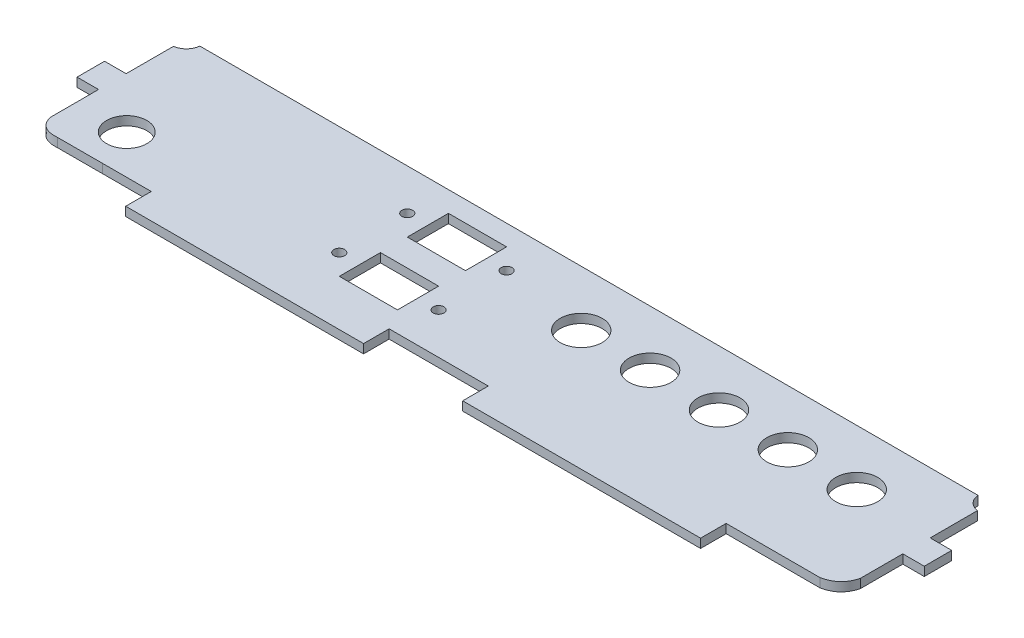
SolidWorks part; units mm, degrees
ref_plane "Front Plane" through (0, 0, 0) normal (0, 0, 1) x (1, 0, 0)
ref_plane "Top Plane" through (0, 0, 0) normal (0, 1, 0) x (1, 0, 0)
ref_plane "Right Plane" through (0, 0, 0) normal (1, 0, 0) x (0, 0, -1)
sketch "Sketch2" plane through (0, -13.2785, 0) normal (0, 1, 0) x (1, 0, 0)
  line L0 (-103.3818, 12.2614) -> (-102.1895, 12.2614) construction
  line L1 (-103.3844, 15.727) -> (-103.3793, 8.7959) construction
  line L2 (-33.2889, 12.2828) -> (-34.6519, 12.2828) construction
  line L3 (-33.2915, 15.7744) -> (-33.2863, 8.7912) construction
  line L4 (-34.6519, 12.2828) -> (-34.6519, 8.7913)
  line L5 (-103.3793, 8.7959) -> (-33.2863, 8.7912) construction
  line L6 (-34.6519, 8.7913) -> (-102.1895, 8.7958)
  line L7 (-116.0844, 15.783) -> (-116.0844, 16.0521) construction
  line L9 (-128.7844, 15.783) -> (-103.3844, 15.783) construction
  line L10 (-116.0844, 16.0521) -> (-102.1895, 16.0521)
  line L11 (-102.1895, 16.0521) -> (-102.1895, 12.2614)
  line L12 (-102.1895, 12.2614) -> (-102.1895, 8.7958)
  line L13 (93.8498, 21.5902) -> (93.5958, 21.5902) construction
  line L14 (-34.6519, 12.2828) -> (-34.6519, 16.0521)
  line L15 (-128.7844, 15.783) -> (-128.7844, 16.037)
  line L17 (93.5958, 21.5902) -> (93.5958, 33.6447)
  line L18 (67.0981, 58.9572) -> (67.0981, 58.7032) construction
  line L28 (90.1543, 58.9557) -> (-131.3147, 58.9704) construction
  line L30 (67.0981, 58.7032) -> (-108.2542, 58.7032)
  line L31 (67.0981, 58.7032) -> (89.8898, 58.7032)
  line L33 (-108.2542, 58.7032) -> (-131.0459, 58.7032)
  line L35 (-20.5781, 8.7904) -> (-20.5781, 74.1189) construction
  line L36 (-7.8698, 8.7896) -> (-33.2863, 8.7912) construction
  line L39 (99.6888, 41.4461) -> (93.5672, 41.4461)
  line L40 (99.6893, 33.6447) -> (99.6888, 41.4461)
  line L41 (96.7684, 33.6447) -> (99.6893, 33.6447)
  line L42 (96.7684, 33.6447) -> (93.5958, 33.6447)
  line L44 (74.9283, 16.0521) -> (87.6283, 16.0521)
  line L45 (74.9283, 16.0521) -> (61.0334, 16.0521)
  line L46 (61.0334, 16.0521) -> (61.0334, 12.2614)
  line L47 (61.0334, 12.2614) -> (61.0334, 8.7958)
  line L48 (-6.5042, 8.7913) -> (61.0334, 8.7958)
  line L49 (-6.5042, 12.2828) -> (-6.5042, 16.0521)
  line L50 (-6.5042, 12.2828) -> (-6.5042, 8.7913)
  line L52 (-34.6519, 16.0521) -> (-6.5042, 16.0521)
  line L53 (-128.7844, 16.037) -> (-116.0844, 16.0521)
  line L54 (93.852, 55.149) -> (93.852, 54.895) construction
  line L55 (93.8512, 42.7342) -> (93.852, 55.149) construction
  line L56 (93.852, 54.895) -> (93.5672, 54.895) construction
  line L57 (93.5672, 54.895) -> (93.5672, 41.4461)
  line L58 (91.7303, 17.7562) -> (91.555, 17.94) construction
  line L59 (-134.7233, 54.895) -> (-134.7233, 41.4461)
  line L60 (-140.8449, 41.4461) -> (-134.7233, 41.4461)
  line L61 (-140.8454, 33.6447) -> (-140.8449, 41.4461)
  line L62 (-137.9245, 33.6447) -> (-140.8454, 33.6447)
  line L63 (-137.9245, 33.6447) -> (-134.7519, 33.6447)
  line L64 (-133.7195, 17.34) -> (-133.5371, 17.5168) construction
  line L65 (-135.0043, 20.0095) -> (-134.7503, 20.0095) construction
  line L66 (-134.7503, 20.0095) -> (-134.7519, 33.6447)
  arc A2 (89.8898, 58.7032) -> (93.5672, 54.895) centre (94.0894, 59.0788) ccw
  arc A4 (-131.0459, 58.7032) -> (-134.7233, 54.895) centre (-135.2455, 59.0788) cw
  parabola Q0 (93.41, 55.3299) -> (93.9736, 52.613) focus (90.4097, 55.3992) apex (92.2035, 57.193) construction
  parabola Q2 (87.6236, 15.783) -> (93.8498, 21.5902) focus (89.4284, 20.1682) apex (91.7303, 17.7562) construction
  parabola Q3 (-128.7844, 15.783) -> (-135.0043, 20.0095) focus (-132.2057, 18.8084) apex (-133.7195, 17.34) construction
  spline S0 degree 2 poles (-134.7503, 20.0095) (-133.7714, 15.691) (-128.7844, 16.037) knots 0 0 0 1 1 1
  spline S1 degree 2 poles (87.6283, 16.0521) (92.3764, 16.9445) (93.5958, 21.5902) knots 0 0 0 1 1 1
  point P33 (-20.5781, 58.7032)
  dimension "D1" = 0.254
  dimension "D2" = 0.2848
extrude "Boss-Extrude1" add sketch "Sketch2" along normal blind 2.54
sketch "Sketch3" plane through (0, -10.7385, 0) normal (0, 1, 0) x (1, 0, 0)
  line L0 (-20.5781, 16.0521) -> (-20.5781, 58.7032) construction
  line L1 (-34.6519, 16.0521) -> (-6.5042, 16.0521) construction
  line L2 (-131.0459, 58.7032) -> (89.8898, 58.7032) construction
  line L3 (-1.0201, 42.9211) -> (6.5999, 42.9211) construction
  line L4 (6.5999, 42.9211) -> (12.5689, 42.9211) construction
  line L5 (-20.5781, 42.9211) -> (-12.9581, 42.9211) construction
  line L6 (-12.9581, 42.9211) -> (-6.9891, 42.9211) construction
  line L7 (18.5379, 42.9211) -> (26.1579, 42.9211) construction
  line L8 (26.1579, 42.9211) -> (32.1269, 42.9211) construction
  line L9 (38.0959, 42.9211) -> (45.7159, 42.9211) construction
  line L10 (45.7159, 42.9211) -> (51.6849, 42.9211) construction
  line L11 (57.6539, 42.9211) -> (65.2739, 42.9211) construction
  line L12 (65.2739, 42.9211) -> (71.2429, 42.9211) construction
  line L13 (71.2429, 36.9521) -> (71.2429, 16.0521) construction
  line L14 (61.0334, 16.0521) -> (87.6283, 16.0521) construction
  line L15 (71.2429, 16.0521) -> (-20.5781, 16.0521) construction
  line L16 (51.6849, 36.9521) -> (51.6849, 16.0521) construction
  line L17 (32.1269, 36.9521) -> (32.1269, 16.0521) construction
  line L18 (12.5689, 36.9521) -> (12.5689, 16.0521) construction
  line L19 (-6.9891, 36.9521) -> (-6.9891, 16.0521) construction
  circle A0 centre (-6.9891, 42.9211) radius 5.969
  circle A1 centre (12.5689, 42.9211) radius 5.969
  circle A2 centre (32.1269, 42.9211) radius 5.969
  circle A3 centre (51.6849, 42.9211) radius 5.969
  circle A4 centre (71.2429, 42.9211) radius 5.969
  dimension "D1" = 11.938
  dimension "D2" = 11.938
  dimension "D3" = 11.938
  dimension "D4" = 11.938
  dimension "D5" = 11.938
  dimension "D6" = 20.9
extrude "Cut-Extrude1" cut sketch "Sketch3" against normal blind 2.54
sketch "Sketch4" plane through (0, -10.7385, 0) normal (0, 1, 0) x (1, 0, 0)
  line L0 (-20.5781, 16.0521) -> (-20.5781, 58.7032) construction
  line L1 (-34.6519, 16.0521) -> (-6.5042, 16.0521) construction
  line L2 (-131.0459, 58.7032) -> (89.8898, 58.7032) construction
  line L3 (-20.5781, 37.3776) -> (-121.2998, 37.3776) construction
  line L4 (-46.3761, 37.3776) -> (-46.3761, 41.1876) construction
  line L5 (-46.3761, 37.3776) -> (-46.3761, 33.5676) construction
  line L6 (-46.3761, 41.1876) -> (-46.3761, 52.8716) construction
  line L7 (-46.3761, 47.0296) -> (-33.8031, 47.0296) construction
  line L8 (-46.3761, 47.0296) -> (-58.9491, 47.0296) construction
  line L9 (-33.8031, 47.0296) -> (-30.7551, 47.0296) construction
  line L10 (-58.9491, 47.0296) -> (-61.9971, 47.0296) construction
  line L11 (-54.6311, 41.1876) -> (-38.1211, 41.1876)
  line L12 (-38.1211, 41.1876) -> (-38.1211, 52.8716)
  line L13 (-38.1211, 52.8716) -> (-54.6311, 52.8716)
  line L14 (-54.6311, 41.1876) -> (-54.6311, 52.8716)
  line L15 (-38.1211, 33.5676) -> (-38.1211, 21.8836)
  line L16 (-38.1211, 21.8836) -> (-54.6311, 21.8836)
  line L17 (-54.6311, 33.5676) -> (-54.6311, 21.8836)
  line L18 (-54.6311, 33.5676) -> (-38.1211, 33.5676)
  circle A0 centre (-32.2791, 47.0296) radius 1.524
  circle A1 centre (-60.4731, 47.0296) radius 1.524
  circle A2 centre (-60.4731, 27.7256) radius 1.524
  circle A3 centre (-32.2791, 27.7256) radius 1.524
  dimension "D1" = 3.048
extrude "Cut-Extrude2" cut sketch "Sketch4" against normal blind 2.54
sketch "Sketch5" plane through (0, -10.7385, 0) normal (0, 1, 0) x (1, 0, 0)
  circle A1 centre (-120.2833, 27.1852) radius 5.715
extrude "Cut-Extrude3" cut sketch "Sketch5" against normal blind 2.54
sketch "Sketch6" plane through (0, -13.2785, 0) normal (0, -1, 0) x (1, 0, 0)
  text T0 "Power in" font "Impact" height 3.5
  text T1 "P1" font "Impact" height 3.5
  text T2 "P2" font "Impact" height 3.5
  point P2 (-70.7784, -30.3673)
  point P3 (-69.452, -29.2821)
  point P5 (-61.3017, -37.185)
  point P6 (-69.452, -47.7911)
  point P7 (-69.452, -48.8928)
extrude "Boss-Extrude2" add sketch "Sketch6" along normal blind 1.27
